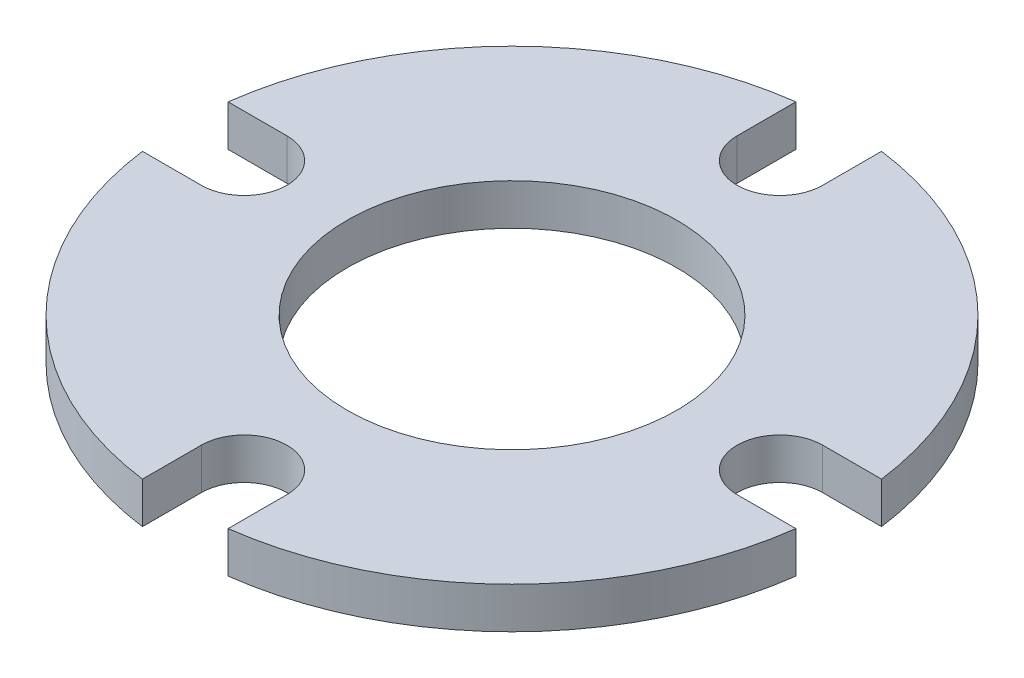
SolidWorks part; units mm, degrees
ref_plane "Front Plane" through (0, 0, 0) normal (0, 0, 1) x (1, 0, 0)
ref_plane "Top Plane" through (0, 0, 0) normal (0, 1, 0) x (1, 0, 0)
ref_plane "Right Plane" through (0, 0, 0) normal (1, 0, 0) x (0, 0, -1)
sketch "Sketch2" plane through (0, 0, 0) normal (0, 1, 0) x (1, 0, 0)
  line L1 (20.6502, -3.302) -> (25.1845, -3.302)
  line L2 (20.6502, 3.302) -> (25.1845, 3.302)
  line L3 (3.302, -20.6502) -> (3.302, -25.1845)
  line L4 (-3.302, -20.6502) -> (-3.302, -25.1845)
  line L5 (-20.6502, -3.302) -> (-25.1845, -3.302)
  line L6 (-20.6502, 3.302) -> (-25.1845, 3.302)
  line L7 (-3.302, 20.6502) -> (-3.302, 25.1845)
  line L8 (3.302, 20.6502) -> (3.302, 25.1845)
  arc A0 (25.1845, 3.302) -> (3.302, 25.1845) centre (0, 0) ccw
  arc A1 (20.6502, 3.302) -> (20.6502, -3.302) centre (20.6502, 0) ccw
  arc A2 (3.302, -20.6502) -> (-3.302, -20.6502) centre (0, -20.6502) ccw
  arc A3 (-20.6502, -3.302) -> (-20.6502, 3.302) centre (-20.6502, 0) ccw
  arc A4 (-3.302, 20.6502) -> (3.302, 20.6502) centre (0, 20.6502) ccw
  arc A5 (-3.302, 25.1845) -> (-25.1845, 3.302) centre (0, 0) ccw
  arc A6 (-25.1845, -3.302) -> (-3.302, -25.1845) centre (0, 0) ccw
  arc A7 (3.302, -25.1845) -> (25.1845, -3.302) centre (0, 0) ccw
  point P5 (20.6502, 25.4)
  point P6 (20.6502, -25.4)
  point P29 (0, 0)
  dimension "D1" = 50.8
  dimension "D2" = 4
extrude "Boss-Extrude1" add sketch "Sketch2" along normal blind 3.175
sketch "Sketch3" plane through (0, 3.175, 0) normal (0, 1, 0) x (1, 0, 0)
  circle A0 centre (0, 0) radius 12.7
  dimension "D1" = 25.4
extrude "Cut-Extrude1" cut sketch "Sketch3" against normal blind 3.175 contours A0
